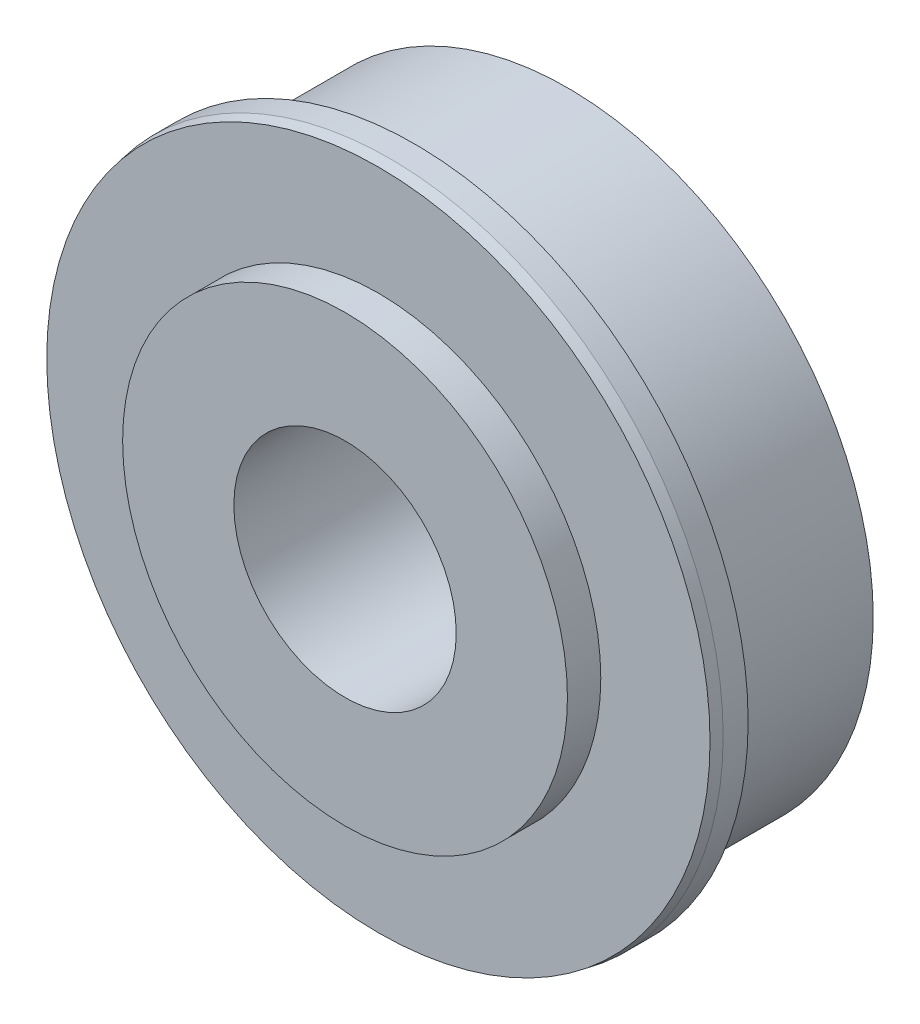
SolidWorks part; units mm, degrees
material "1023 Carbon Steel Sheet (SS)"
ref_plane "Front Plane" through (0, 0, 0) normal (1, 0, 0) x (0, 1, 0)
ref_plane "Top Plane" through (0, 0, 0) normal (0, 0, 1) x (0, 1, 0)
ref_plane "Right Plane" through (0, 0, 0) normal (0, 1, 0) x (-1, 0, 0)
sketch "Sketch1" plane through (0, 0, 0) normal (0, 1, 0) x (-1, 0, 0)
  line L0 (0, 114.8517) -> (0, -101.7673) construction
  line L1 (-17.4625, -6.35) -> (-17.4625, 1.7462)
  line L2 (-17.4625, 1.7462) -> (-17.3505, 2.3812)
  line L3 (-17.3505, 2.3812) -> (-19.05, 2.3812)
  line L4 (-19.05, 2.3812) -> (-19.05, 3.81)
  line L5 (-19.05, 3.81) -> (-18.938, 4.445)
  line L9 (-6.35, 6.35) -> (-6.35, -6.35)
  line L10 (-12.7, 6.35) -> (-6.35, 6.35)
  line L11 (-17.4625, -6.35) -> (-6.35, -6.35)
  line L12 (-17.4625, 1.7462) -> (-17.4625, 2.3812) construction
  line L13 (-18.938, 4.445) -> (-12.7, 4.445)
  line L14 (-12.7, 4.445) -> (-12.7, 6.35)
  line L15 (-18.938, 4.445) -> (-18.938, 3.81) construction
  line L16 (-18.938, 3.81) -> (-19.05, 3.81) construction
  line L17 (-6.35, 0) -> (0, 0) construction
  point P10 (-6.35, -2.4487)
  point P12 (-17.4625, -8.7987)
  point P14 (0, 0)
  point P15 (-14.0332, -3.1646)
  point P18 (-18.938, 5.3814)
  point P19 (-12.7, 4.7805)
  dimension "D1" = 12.7
  dimension "D2" = 34.925
  dimension "D3" = 10
  dimension "D4" = 38.1
  dimension "D5" = 12.7
  dimension "D6" = 3.9688
  dimension "D7" = 0.635
  dimension "D8" = 0.635
  dimension "D9" = 25.4
  dimension "D10" = 1.905
revolve "Revolve1" add sketch "Sketch1" angle 360 about L0
